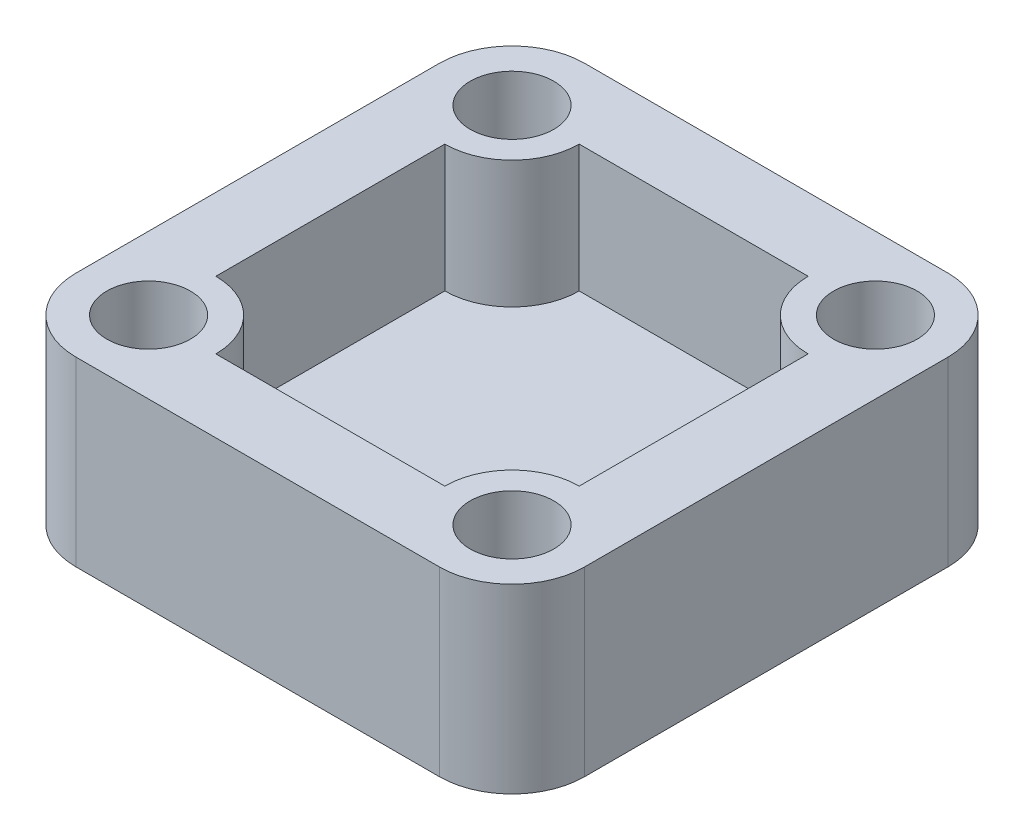
SolidWorks part; units mm, degrees
ref_plane "Спереди" through (0, 0, 0) normal (0, 0, 1) x (1, 0, 0)
ref_plane "Сверху" through (0, 0, 0) normal (0, 1, 0) x (1, 0, 0)
ref_plane "Справа" through (0, 0, 0) normal (1, 0, 0) x (0, 0, -1)
sketch "Sketch1" plane through (0, 0, 0) normal (0, 1, 0) x (1, 0, 0)
  line L0 (0, 0) -> (0, 7) construction
  line L1 (-5, -5) -> (5, -5) construction
  line L2 (-5, -5) -> (-5, 5) construction
  line L3 (-5, 5) -> (5, 5) construction
  line L4 (5, -5) -> (5, 5) construction
  line L5 (-5, -5) -> (5, 5) construction
  line L6 (-5, 5) -> (5, -5) construction
  line L7 (0, 0) -> (7, 0) construction
  line L8 (0, 7) -> (5, 7)
  line L9 (7, 0) -> (7, 5)
  line L10 (7, 0) -> (7, -5)
  line L11 (0, -7) -> (5, -7)
  line L12 (0, -7) -> (-5, -7)
  line L13 (-7, 0) -> (-7, -5)
  line L14 (-7, 0) -> (-7, 5)
  line L15 (0, 7) -> (-5, 7)
  arc A0 (5, 7) -> (7, 5) centre (5, 5) cw
  arc A1 (7, -5) -> (5, -7) centre (5, -5) cw
  arc A2 (-5, -7) -> (-7, -5) centre (-5, -5) cw
  arc A3 (-7, 5) -> (-5, 7) centre (-5, 5) cw
  point P0 (0, 0)
  point P30 (0, 0)
  dimension "D1" = 10
  dimension "D2" = 10
  dimension "D3" = 2
  dimension "D4" = 2
  dimension "D5" = 4
extrude "Boss-Extrude1" add sketch "Sketch1" along normal blind 1.5
sketch "Sketch2" plane through (0, 1.5, 0) normal (0, 1, 0) x (1, 0, 0)
  line L0 (-5, 5) -> (5, 5) construction
  line L1 (5, -5) -> (5, 5) construction
  line L2 (0, 5) -> (3.15, 5)
  line L3 (5, 3.15) -> (5, 0)
  line L4 (7, 0) -> (7, 5) construction
  line L5 (0, 7) -> (5, 7)
  line L6 (7, 5) -> (7, 0)
  line L7 (7, 0) -> (7, -5)
  line L8 (5, -7) -> (0, -7)
  line L9 (3.15, -5) -> (0, -5)
  line L10 (5, 0) -> (5, -3.15)
  line L11 (0, -7) -> (-5, -7)
  line L12 (-7, -5) -> (-7, 0)
  line L13 (-5, -3.15) -> (-5, 0)
  line L14 (0, -5) -> (-3.15, -5)
  line L15 (-7, 0) -> (-7, 5)
  line L16 (-5, 7) -> (0, 7)
  line L17 (-3.15, 5) -> (0, 5)
  line L18 (-5, 0) -> (-5, 3.15)
  arc A0 (3.15, 5) -> (5, 3.15) centre (5, 5) ccw
  arc A1 (5, 7) -> (7, 5) centre (5, 5) cw
  arc A2 (7, -5) -> (5, -7) centre (5, -5) cw
  arc A3 (5, -3.15) -> (3.15, -5) centre (5, -5) ccw
  arc A4 (-5, -7) -> (-7, -5) centre (-5, -5) cw
  arc A5 (-3.15, -5) -> (-5, -3.15) centre (-5, -5) ccw
  arc A6 (-7, 5) -> (-5, 7) centre (-5, 5) cw
  arc A7 (-5, 3.15) -> (-3.15, 5) centre (-5, 5) ccw
  point P49 (0, 0)
  dimension "D1" = 1.85
  dimension "D2" = 4
extrude "Boss-Extrude2" add sketch "Sketch2" along normal blind 3.5
sketch "Sketch3" plane through (0, 5, 0) normal (0, 1, 0) x (1, 0, 0)
  circle A0 centre (5, 5) radius 1.15
  circle A1 centre (5, -5) radius 1.15
  circle A2 centre (-5, -5) radius 1.15
  circle A3 centre (-5, 5) radius 1.15
  point P12 (0, 0)
  dimension "D1" = 2.3
  dimension "D2" = 4
extrude "Cut-Extrude1" cut sketch "Sketch3" against normal through all
